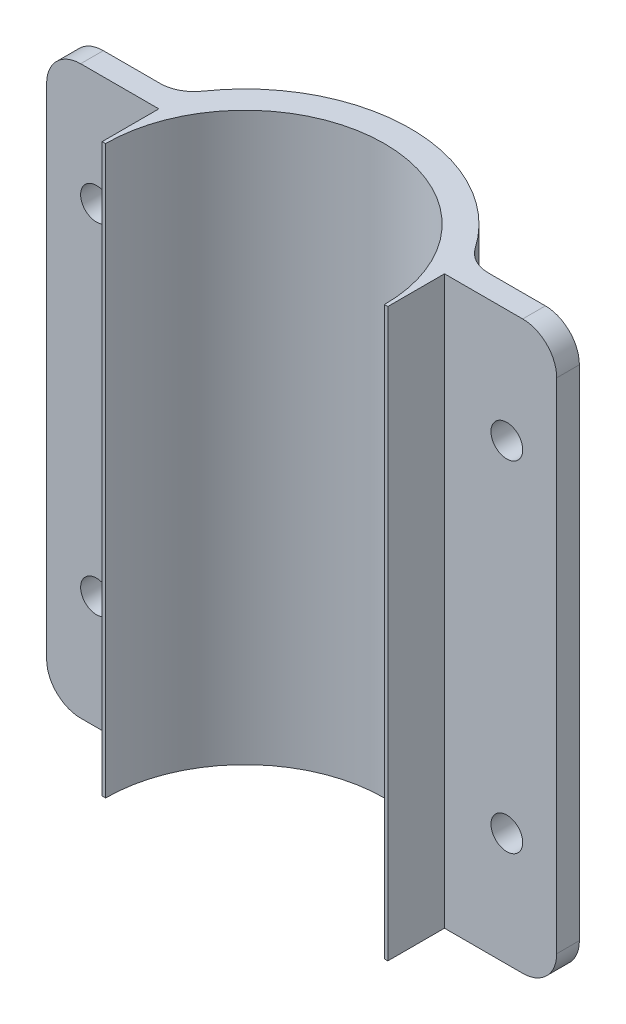
SolidWorks part; units mm, degrees
ref_plane "Front Plane" through (0, 0, 0) normal (0, 0, 1) x (1, 0, 0)
ref_plane "Top Plane" through (0, 0, 0) normal (0, 1, 0) x (1, 0, 0)
ref_plane "Right Plane" through (0, 0, 0) normal (1, 0, 0) x (0, 0, -1)
sketch "Sketch1" plane through (0, 0, 0) normal (0, 1, 0) x (1, 0, 0)
  line L0 (-12.6, 0) -> (-12.6, 5)
  line L2 (12.6, 5) -> (12.6, 0)
  line L4 (-12.6, 5) -> (-22.5, 5)
  line L6 (-22.1, 7) -> (-14.4831, 7)
  line L7 (12.6, 0) -> (12.3, 0)
  line L8 (12.6, 5) -> (22.5, 5)
  line L10 (22.1, 7) -> (14.4831, 7)
  line L11 (-12.3, 0) -> (-12.6, 0)
  line L12 (-22.5, 5) -> (-22.5, 7)
  line L13 (-22.5, 7) -> (-22.1, 7)
  line L14 (22.5, 5) -> (22.5, 7)
  line L15 (22.5, 7) -> (22.1, 7)
  arc A1 (12.0144, 8.2955) -> (-12.0144, 8.2955) centre (0, 0) ccw
  arc A2 (14.4831, 7) -> (12.0144, 8.2955) centre (14.4831, 10) cw
  arc A3 (-14.4831, 7) -> (-12.0144, 8.2955) centre (-14.4831, 10) ccw
  arc A4 (12.3, 0) -> (-12.3, 0) centre (0, 0) ccw
  dimension "D1" = 3
extrude "Boss-Extrude1" add sketch "Sketch1" along normal blind 50 contours L6 A3 A1 A2 L10 L15 L14 L8 L2 L7 A4 L11 L0 L4 L12 L13
sketch "Sketch2" plane through (0, 0, -7) normal (0, 0, -1) x (-1, 0, 0)
  circle A9 centre (-18.1, 10) radius 1.4
  circle A10 centre (-18.1, 40) radius 1.4
  circle A11 centre (18.1, 40) radius 1.4
  circle A12 centre (18.1, 10) radius 1.4
extrude "Cut-Extrude3" cut sketch "Sketch2" against normal blind 2
fillet "Fillet2" radius 3 4 edges at (22.5, 0, -6) (-22.5, 0, -6) (-22.5, 50, -6) (22.5, 50, -6)
